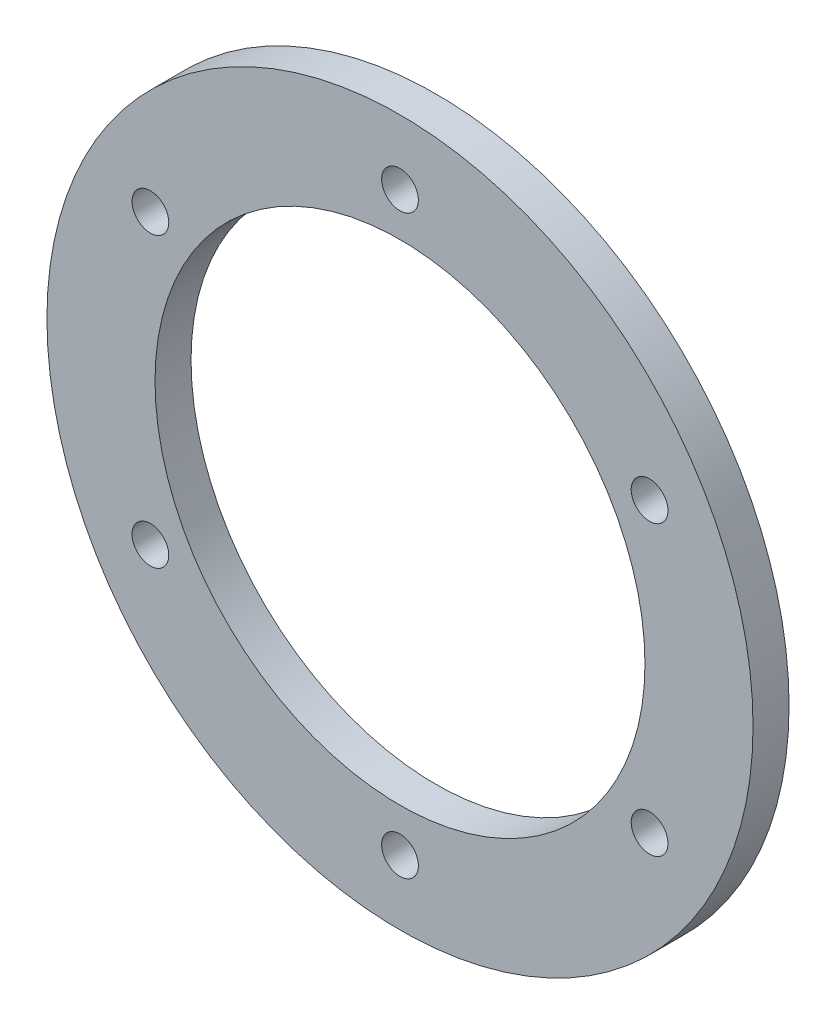
SolidWorks part; units mm, degrees
ref_plane "Front Plane" through (0, 0, 0) normal (0, 0, 1) x (1, 0, 0)
ref_plane "Top Plane" through (0, 0, 0) normal (0, 1, 0) x (1, 0, 0)
ref_plane "Right Plane" through (0, 0, 0) normal (1, 0, 0) x (0, 0, -1)
sketch "Sketch1" plane through (0, 0, 0) normal (0, 0, 1) x (1, 0, 0)
  circle A0 centre (0, 0) radius 34
  circle A1 centre (0, 0) radius 49
extrude "Boss-Extrude1" add sketch "Sketch1" along normal blind 5
sketch "Sketch2" plane through (0, 0, 0) normal (0, 0, 1) x (1, 0, 0)
  line L0 (0, 0) -> (0, 40) construction
  circle A0 centre (0, 0) radius 40 construction
  circle A1 centre (0, 40) radius 2.55
  circle A2 centre (34.641, 20) radius 2.55
  circle A3 centre (34.641, -20) radius 2.55
  circle A4 centre (0, -40) radius 2.55
  circle A5 centre (-34.641, -20) radius 2.55
  circle A6 centre (-34.641, 20) radius 2.55
  point P16 (0, 0)
  dimension "D1" = 6
extrude "Cut-Extrude1" cut sketch "Sketch2" along normal through all
